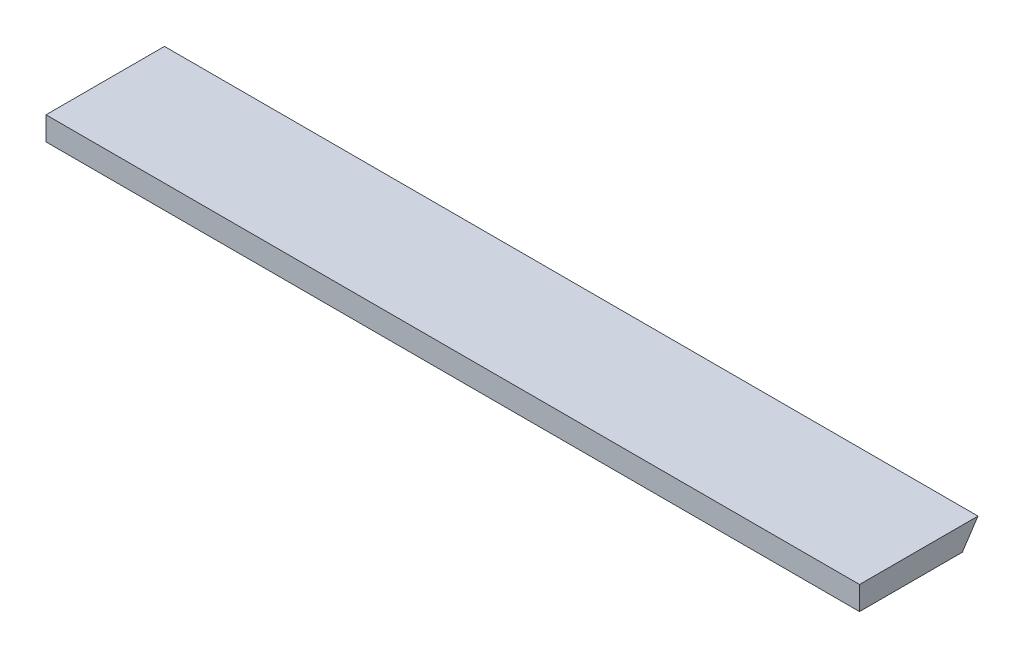
SolidWorks part; units mm, degrees
ref_plane "Front Plane" through (0, 0, 0) normal (0, 0, 1) x (1, 0, 0)
ref_plane "Top Plane" through (0, 0, 0) normal (0, 1, 0) x (1, 0, 0)
ref_plane "Right Plane" through (0, 0, 0) normal (1, 0, 0) x (0, 0, -1)
sketch "Sketch1" plane through (0, 0, 0) normal (0, 1, 0) x (1, 0, 0)
  line L0 (-93.273, 5.1913) -> (183.727, 5.1913)
  line L1 (-93.273, 5.1913) -> (-93.273, 40.1913)
  line L2 (-93.273, 40.1913) -> (183.727, 40.1913)
  line L3 (183.727, 40.1913) -> (183.727, 5.1913)
extrude "Boss-Extrude1" add sketch "Sketch1" along normal blind 8
sketch "Sketch2" plane through (-93.273, 0, 0) normal (-1, 0, 0) x (0, 0, 1)
  line L0 (-40.1913, 0) -> (-45.5246, 8)
  line L3 (-40.1913, 8) -> (-40.1913, 0) construction
  line L4 (-40.1913, 8) -> (-45.5246, 8)
  line L5 (-40.1913, 8) -> (-40.1913, 0)
  dimension "D1" = 33.69
extrude "Boss-Extrude2" add sketch "Sketch2" against normal blind 277
